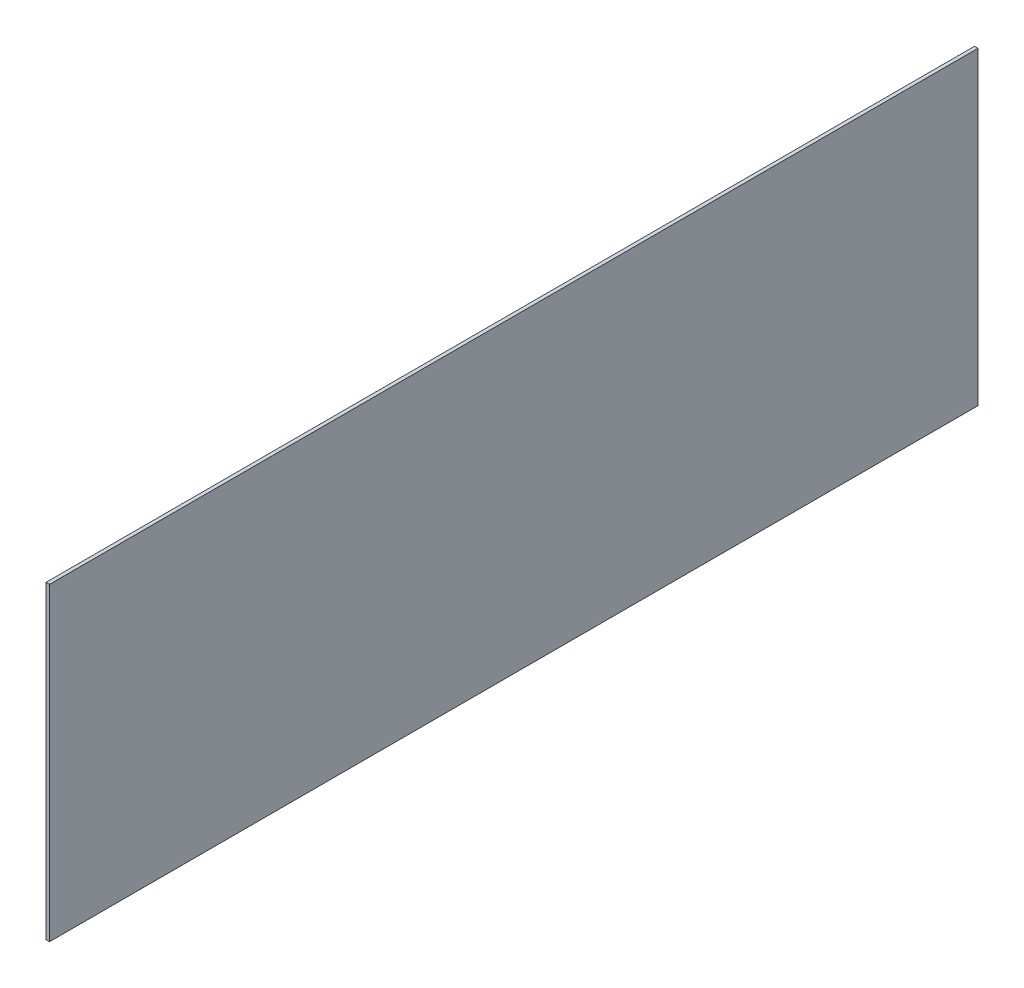
SolidWorks part; units mm, degrees
ref_plane "Front Plane" through (0, 0, 0) normal (0, 0, 1) x (1, 0, 0)
ref_plane "Top Plane" through (0, 0, 0) normal (0, 1, 0) x (1, 0, 0)
ref_plane "Right Plane" through (0, 0, 0) normal (1, 0, 0) x (0, 0, -1)
sketch "Sketch1" plane through (0, 0, 0) normal (1, 0, 0) x (0, 0, -1)
  line L1 (0, 0) -> (419.1, 0)
  line L2 (0, 0) -> (0, 139.7)
  line L3 (0, 139.7) -> (419.1, 139.7)
  line L4 (419.1, 0) -> (419.1, 139.7)
  dimension "D1" = 139.7
  dimension "D2" = 419.1
extrude "Boss-Extrude1" add sketch "Sketch1" along normal blind 1.5875
